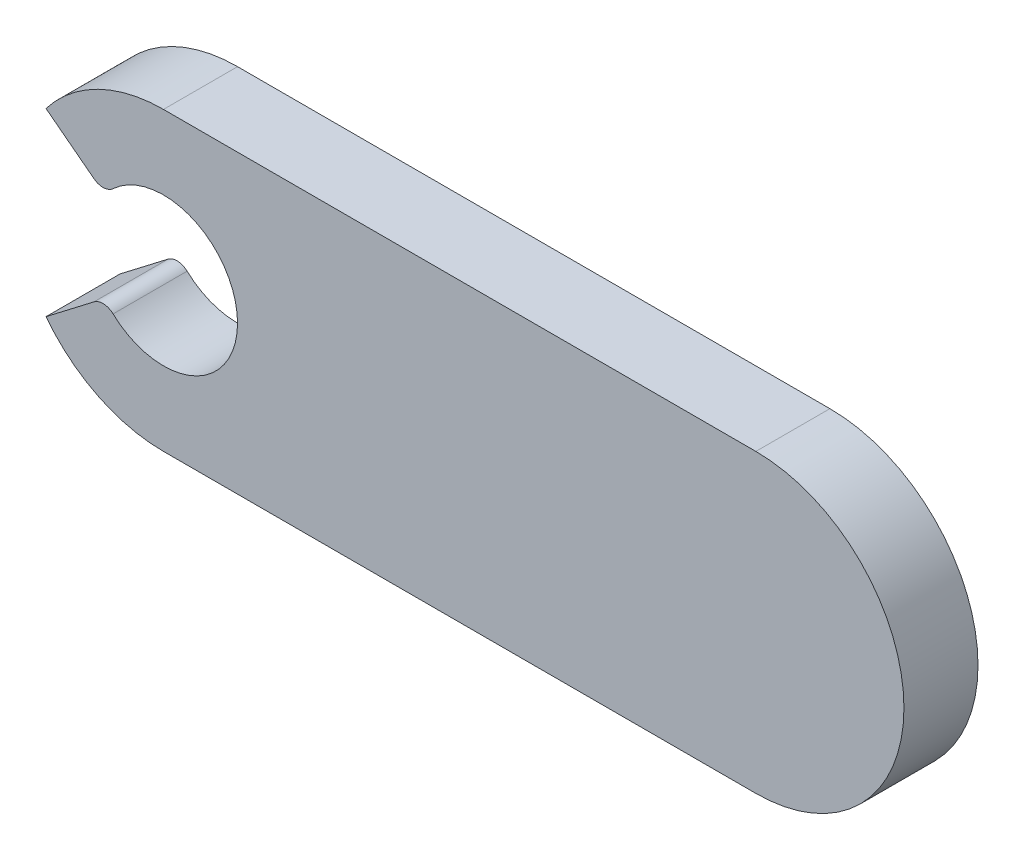
SolidWorks part; units mm, degrees
ref_plane "Front Plane" through (0, 0, 0) normal (0, 0, 1) x (1, 0, 0)
ref_plane "Top Plane" through (0, 0, 0) normal (0, 1, 0) x (1, 0, 0)
ref_plane "Right Plane" through (0, 0, 0) normal (1, 0, 0) x (0, 0, -1)
sketch "Sketch1" plane through (0, 0, 0) normal (0, 0, 1) x (1, 0, 0)
  line L0 (-3.9668, 3.0438) -> (-1.9834, 1.5219)
  line L1 (-1.9834, -1.5219) -> (-3.9668, -3.0438)
  line L2 (0, 5) -> (20, 5)
  line L3 (20, -5) -> (0, -5)
  arc A0 (-3.9668, 3.0438) -> (0, 5) centre (0, 0) cw
  arc A1 (-1.9834, 1.5219) -> (-1.9834, -1.5219) centre (0, 0) cw
  arc A2 (20, 5) -> (20, -5) centre (20, 0) cw
  arc A3 (0, -5) -> (-3.9668, -3.0438) centre (0, 0) cw
  point P10 (0, 0)
  point P12 (0, 0)
  point P13 (0, 0)
  point P14 (0, 0)
  point P15 (38.4704, 0)
  point P16 (0, -5)
  point P17 (24.0829, -3.0438)
  dimension "D2" = 2.5
  dimension "D3" = 5
  dimension "D4" = 20
  dimension "D1" = 75
extrude "Boss-Extrude1" add sketch "Sketch1" along normal blind 2.5
fillet "Fillet1" radius 0.5 2 edges at (-1.9834, 1.5219, 1.25) (-1.9834, -1.5219, 1.25)
